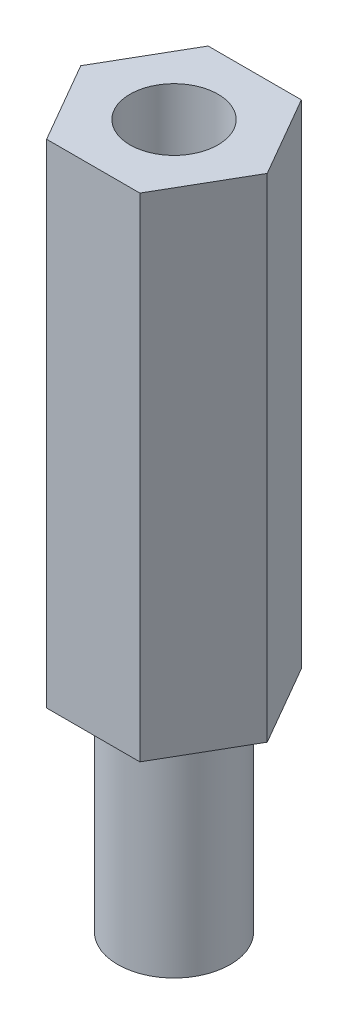
SolidWorks part; units mm, degrees
ref_plane "前视基准面" through (0, 0, 0) normal (0, 0, 1) x (1, 0, 0)
ref_plane "上视基准面" through (0, 0, 0) normal (0, 1, 0) x (1, 0, 0)
ref_plane "右视基准面" through (0, 0, 0) normal (1, 0, 0) x (0, 0, -1)
sketch "草图4" plane through (0, 0, 0) normal (0, 1, 0) x (1, 0, 0)
  line L0 (-12.7945, 0) -> (16.3015, 0) construction
  line L2 (1.325, -2.295) -> (2.65, 0)
  line L3 (2.65, 0) -> (1.325, 2.295)
  line L4 (1.325, 2.295) -> (-1.325, 2.295)
  line L5 (-1.325, 2.295) -> (-2.65, 0)
  line L6 (-2.65, 0) -> (-1.325, -2.295)
  line L7 (-1.325, -2.295) -> (1.325, -2.295)
  circle A0 centre (0, 0) radius 2.295 construction
  dimension "D1" = 5.3
extrude "凸台-拉伸1" add sketch "草图4" along normal blind 14
sketch "草图6" plane through (0, 0, 0) normal (0, -1, 0) x (-1, 0, 0)
  circle A0 centre (0, 0) radius 1.6
  dimension "D1" = 3.2
extrude "凸台-拉伸2" add sketch "草图6" along normal blind 6
cosmetic thread "装饰螺纹线1" parameters "D2"=2.5
sketch "草图7" plane through (0, 14, 0) normal (0, 1, 0) x (1, 0, 0)
  circle A0 centre (0, 0) radius 1.25
  dimension "D1" = 2.5
extrude "切除-拉伸1" cut sketch "草图7" against normal blind 5
cosmetic thread "装饰螺纹线2" parameters "D2"=3
